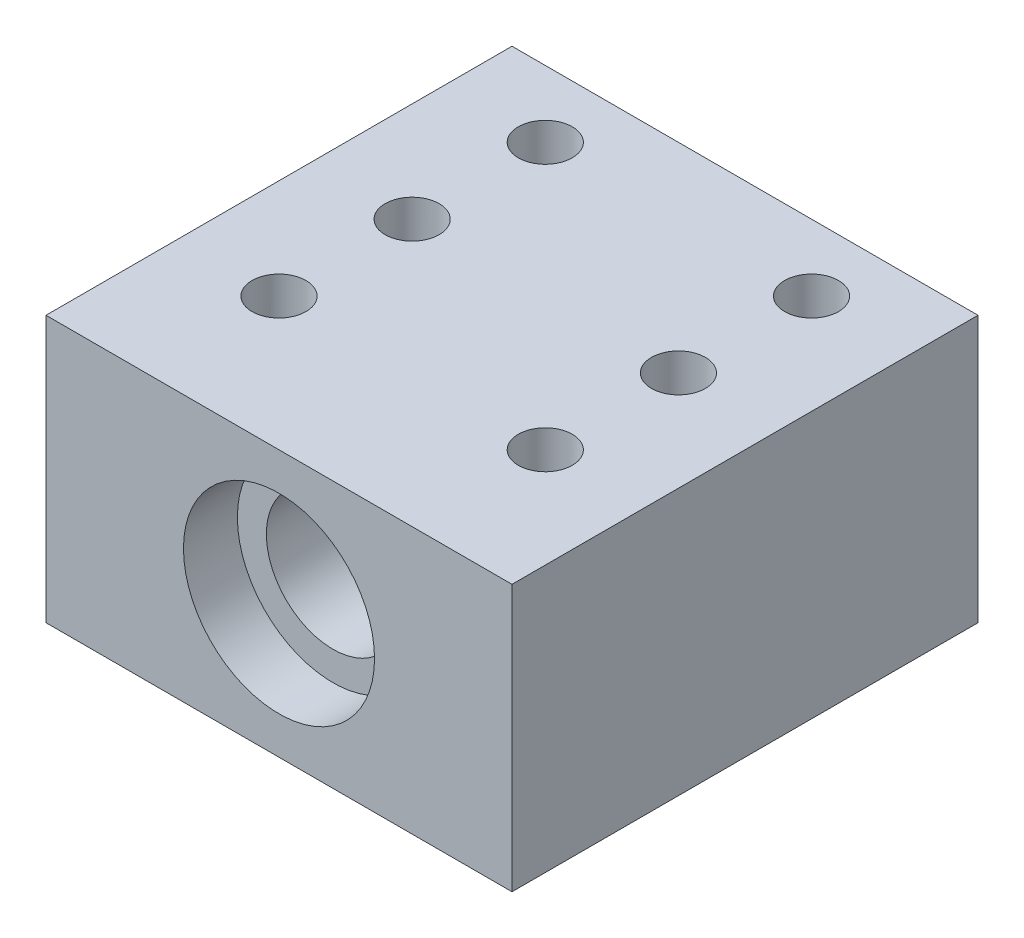
SolidWorks part; units mm, degrees
material "6061 Alloy"
ref_plane "Front Plane" through (0, 0, 0) normal (0, 0, 1) x (1, 0, 0)
ref_plane "Top Plane" through (0, 0, 0) normal (0, 1, 0) x (1, 0, 0)
ref_plane "Right Plane" through (0, 0, 0) normal (1, 0, 0) x (0, 0, -1)
sketch "Sketch1" plane through (0, 0, 0) normal (0, 0, 1) x (1, 0, 0)
  line L0 (0, 0) -> (0, -20) construction
  line L1 (-35, 20) -> (35, 20)
  line L2 (-35, 20) -> (-35, -20)
  line L3 (-35, -20) -> (35, -20)
  line L4 (35, 20) -> (35, -20)
  circle A0 centre (0, 0) radius 10
  circle A1 centre (0, 0) radius 14.2875 construction
  dimension "D1" = 20
  dimension "D2" = 20
  dimension "D5" = 28.575
  dimension "D3" = 20
  dimension "D4" = 70
extrude "Boss-Extrude1" add sketch "Sketch1" against normal blind 30 and the other way blind 40
sketch "Sketch2" plane through (0, 0, 0) normal (0, 1, 0) x (1, 0, 0)
  line L0 (0, 0) -> (0, 20) construction
  line L2 (-20, 20) -> (20, 20) construction
  line L3 (20, -20) -> (-20, -20) construction
  line L4 (20, -20) -> (20, 20) construction
  line L5 (20, 20) -> (-20, 20) construction
  line L6 (-20, -20) -> (-20, 20) construction
  line L7 (20, -20) -> (-20, 20) construction
  line L8 (20, 20) -> (-20, -20) construction
  circle A0 centre (-20, 20) radius 4.05
  circle A1 centre (20, 20) radius 4.05
  circle A2 centre (0, 5) radius 2.5 construction
  circle A3 centre (-20, -20) radius 4.05
  circle A4 centre (20, -20) radius 4.05
  circle A5 centre (-20, 0) radius 4.05
  circle A6 centre (20, 0) radius 4.05
  dimension "D1" = 8.1
  dimension "D4" = 5
  dimension "D5" = 5
  dimension "D3" = 40
extrude "Cut-Extrude1" cut sketch "Sketch2" against normal blind 25 and the other way blind 25
sketch "Sketch3" plane through (0, 0, 0) normal (0, 0, 1) x (1, 0, 0)
  line L0 (-25, 0) -> (25, 0) construction
  circle A0 centre (0, 0) radius 14.35
  dimension "D1" = 28.7
  dimension "D3" = 25
extrude "Cut-Extrude2" cut sketch "Sketch3" against normal blind 8.1 from surface at 40 starting at face at (0, 0, 40)
sketch "Sketch4" plane through (0, 0, 0) normal (0, 0, 1) x (1, 0, 0)
  circle A0 centre (0, 0) radius 14.2875
  dimension "D1" = 28.575
extrude "Cut-Extrude3" cut sketch "Sketch4" along normal blind 8.1 from surface at -30 starting at face at (10, 0, -30)
